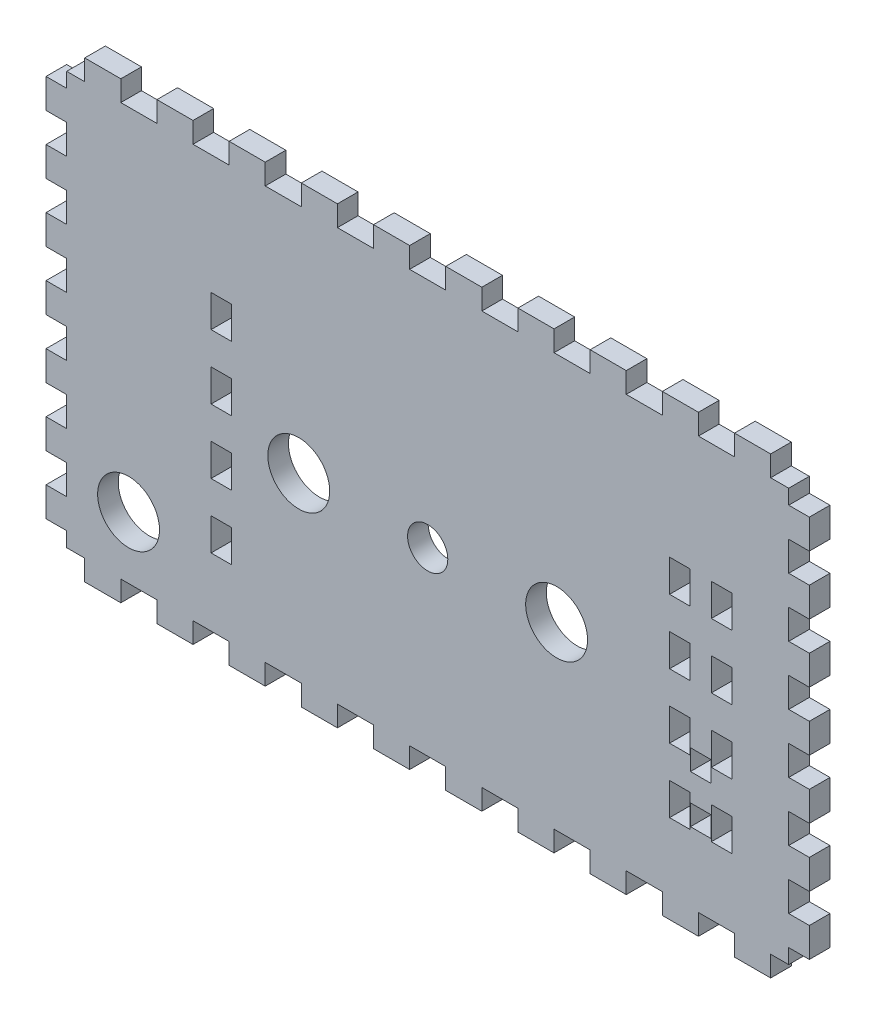
SolidWorks part; units mm, degrees
ref_plane "Piano frontale" through (0, 0, 0) normal (0, 0, 1) x (1, 0, 0)
ref_plane "Piano superiore" through (0, 0, 0) normal (0, 1, 0) x (1, 0, 0)
ref_plane "Piano destro" through (0, 0, 0) normal (1, 0, 0) x (0, 0, -1)
sketch "Schizzo1" plane through (0, 0, 0) normal (0, 0, 1) x (1, 0, 0)
  line L1 (0, 0) -> (140, 0)
  line L2 (0, 0) -> (0, 80)
  line L3 (0, 80) -> (140, 80)
  line L4 (140, 0) -> (140, 80)
  circle A1 centre (45, 35) radius 6
  circle A2 centre (95, 35) radius 6
  circle A3 centre (12, 12) radius 6
  circle A4 centre (70, 35) radius 3.9
  point P9 (70, 0)
  dimension "D3" = 12
  dimension "D4" = 12
  dimension "D8" = 7.8
  dimension "D12" = 12
  dimension "D1" = 140
  dimension "D2" = 80
  dimension "D5" = 35
  dimension "D6" = 25
  dimension "D7" = 25
  dimension "D9" = 70
  dimension "D10" = 12
  dimension "D11" = 12
extrude "Estrusione-Estrusione1" add sketch "Schizzo1" along normal blind 4
sketch "Schizzo2" plane through (0, 0, 4) normal (0, 0, 1) x (1, 0, 0)
  line L0 (0, 80) -> (0, 0) construction
  line L1 (3.5, 80) -> (10.5, 80)
  line L2 (3.5, 80) -> (3.5, 84)
  line L3 (3.5, 84) -> (10.5, 84)
  line L4 (10.5, 80) -> (10.5, 84)
  line L5 (3.5, 0) -> (10.5, 0)
  line L6 (3.5, 0) -> (3.5, -4)
  line L7 (3.5, -4) -> (10.5, -4)
  line L8 (10.5, 0) -> (10.5, -4)
  line L9 (140, 80) -> (0, 80) construction
  line L10 (0, 0) -> (140, 0) construction
  dimension "D1" = 7
  dimension "D2" = 4
  dimension "D4" = 4
  dimension "D3" = 3.5
extrude "Estrusione-Estrusione2" add sketch "Schizzo2" against normal blind 4
pattern_linear "Ripetizione a L1" count 10 spacing 14 along (1, 0, 0) of "Estrusione-Estrusione2"
sketch "Schizzo3" plane through (0, 0, 4) normal (0, 0, 1) x (1, 0, 0)
  line L0 (0, 80) -> (0, 0) construction
  line L1 (0, 77.1429) -> (-4, 77.1429)
  line L2 (0, 77.1429) -> (0, 71.4286)
  line L3 (0, 71.4286) -> (-4, 71.4286)
  line L4 (-4, 77.1429) -> (-4, 71.4286)
  line L5 (140, 0) -> (140, 80) construction
  line L6 (140, 77.1429) -> (144, 77.1429)
  line L7 (140, 77.1429) -> (140, 71.4286)
  line L8 (140, 71.4286) -> (144, 71.4286)
  line L9 (144, 77.1429) -> (144, 71.4286)
  line L10 (140, 80) -> (136.5, 80) construction
  dimension "D4" = 4
  dimension "D1" = 5.7143
  dimension "D2" = 2.8571
  dimension "D3" = 4
extrude "Estrusione-Estrusione3" add sketch "Schizzo3" against normal blind 4
pattern_linear "Ripetizione a L2" count 7 spacing 11.4286 along (0, -1, 0) of "Estrusione-Estrusione3"
sketch "Schizzo4" plane through (0, 0, 4) normal (0, 0, 1) x (1, 0, 0)
  line L1 (28, 56.875) -> (32, 56.875)
  line L2 (28, 56.875) -> (28, 50.625)
  line L3 (28, 50.625) -> (32, 50.625)
  line L4 (32, 56.875) -> (32, 50.625)
  circle A0 centre (95, 35) radius 6 construction
  circle A1 centre (45, 35) radius 6 construction
  dimension "D1" = 4
  dimension "D2" = 6.25
  dimension "D3" = 21.875
  dimension "D4" = 17
extrude "Taglio-Estrusione1" cut sketch "Schizzo4" against normal through all
pattern_linear "Ripetizione a L3" count 4 spacing 12.5 along (0, -1, 0) of "Taglio-Estrusione1"
sketch "Schizzo5" plane through (0, 0, 0) normal (0, 0, -1) x (-1, 0, 0)
  line L0 (-140, 0) -> (-140, 2.8571) construction
  line L1 (-129, 56.875) -> (-125, 56.875)
  line L2 (-129, 56.875) -> (-129, 50.625)
  line L3 (-129, 50.625) -> (-125, 50.625)
  line L4 (-125, 56.875) -> (-125, 50.625)
  line L5 (-120.9, 56.875) -> (-116.9, 56.875)
  line L6 (-120.9, 56.875) -> (-120.9, 50.625)
  line L7 (-120.9, 50.625) -> (-116.9, 50.625)
  line L8 (-116.9, 56.875) -> (-116.9, 50.625)
  line L10 (-32, 56.875) -> (-28, 56.875) construction
  dimension "D1" = 4
  dimension "D2" = 4
  dimension "D3" = 6.25
  dimension "D4" = 11
  dimension "D5" = 4.1
extrude "Taglio-Estrusione2" cut sketch "Schizzo5" against normal through all
pattern_linear "Ripetizione a L4" count 4 spacing 12.5 along (0, -1, 0) of "Taglio-Estrusione2"
sketch "Schizzo6" plane through (0, 0, 0) normal (0, 0, -1) x (-1, 0, 0)
  line L0 (-125, 38.125) -> (-125, 44.375) construction
  line L1 (-124.95, 26.8948) -> (-120.95, 26.8948)
  line L2 (-124.95, 26.8948) -> (-124.95, 22.8948)
  line L3 (-124.95, 22.8948) -> (-120.95, 22.8948)
  line L4 (-120.95, 26.8948) -> (-120.95, 22.8948)
  line L7 (-124.95, 17.6348) -> (-120.95, 17.6348)
  line L8 (-124.95, 17.6348) -> (-124.95, 13.6348)
  line L9 (-124.95, 13.6348) -> (-120.95, 13.6348)
  line L10 (-120.95, 17.6348) -> (-120.95, 13.6348)
  dimension "D1" = 4
  dimension "D2" = 4
  dimension "D3" = 0.05
  dimension "D5" = 9.26
  dimension "D6" = 4
extrude "Taglio-Estrusione3" cut sketch "Schizzo6" against normal through all contours L10 L7 L8 L9 | L1 L4 L3 L2
equation "\"WFront\"= 140mm"
equation "\"HFront\"= 80mm"
equation "\"DFront\"= 4mm"
equation "\"WLeft\"= 50mm"
equation "\"HLeft\"= 80mm"
equation "\"DLeft\"= 4mm"
equation "\"WTop\"= 140mm"
equation "\"HTop\"= 50mm"
equation "\"DTop\"= 4mm"
equation "\"N_Denti_W\"= 10"
equation "\"N_Denti_H\"= 7"
equation "\"N_Denti_D\"= 4"
equation "\"HDistDenti\"= \"HFront\" / \"N_Denti_H\""
equation "\"WDistDenti\"= \"WFront\" / \"N_Denti_W\""
equation "\"DDistDenti\"= \"WLeft\" / \"N_Denti_D\""
equation "\"HDenti\"= \"HDistDenti\" / 2"
equation "\"WDenti\"= \"WDistDenti\" / 2"
equation "\"DDenti\"= \"DDistDenti\" / 2"
equation "\"WDisplay\"= 95mm"
equation "\"HDisplay\"= 61mm"
equation "\"CEnc\"= 7mm"
equation "\"Display_to_Enc_W\"= 11.5 + \"CEnc\" / 2"
equation "\"Display_to_Dx\"= 32mm"
equation "\"Display_to_Top\"= 10mm"
equation "\"Display_to_Enc_H\"= 24 + \"CEnc\" / 2"
equation "\"D1@Schizzo1\"=\"WFront\""
equation "\"D2@Schizzo1\"=\"HFront\""
equation "\"D1@Estrusione-Estrusione1\"=\"DFront\""
equation "\"D1@Schizzo2\"=\"WDenti\""
equation "\"D2@Schizzo2\"=\"DTop\""
equation "\"D4@Schizzo2\"=\"DTop\""
equation "\"D1@Estrusione-Estrusione2\"=\"DFront\""
equation "\"D3@Ripetizione a L1\"=\"WDistDenti\""
equation "\"D1@Ripetizione a L1\"=\"N_Denti_W\""
equation "\"D3@Schizzo2\"=\"WDenti\"/2"
equation "\"D1@Schizzo3\"=\"HDenti\""
equation "\"D2@Schizzo3\"=\"HDenti\"/2"
equation "\"D3@Schizzo3\"=\"DLeft\""
equation "\"D4@Schizzo3\"=\"DLeft\""
equation "\"D1@Estrusione-Estrusione3\"=\"DFront\""
equation "\"D3@Ripetizione a L2\"=\"HDistDenti\""
equation "\"D1@Ripetizione a L2\"=\"N_Denti_H\""
equation "\"DMask\"= 3mm"
equation "\"D1@Schizzo4\"=\"DFront\""
equation "\"D2@Schizzo4\"=\"DDenti\""
equation "\"D3@Schizzo4\"=\"WLeft\"/2 - \"DDenti\"/2"
equation "\"D3@Ripetizione a L3\"=\"DDistDenti\""
equation "\"D1@Ripetizione a L3\"=\"N_Denti_D\""
equation "\"D9@Schizzo1\"=\"WFront\"/2"
